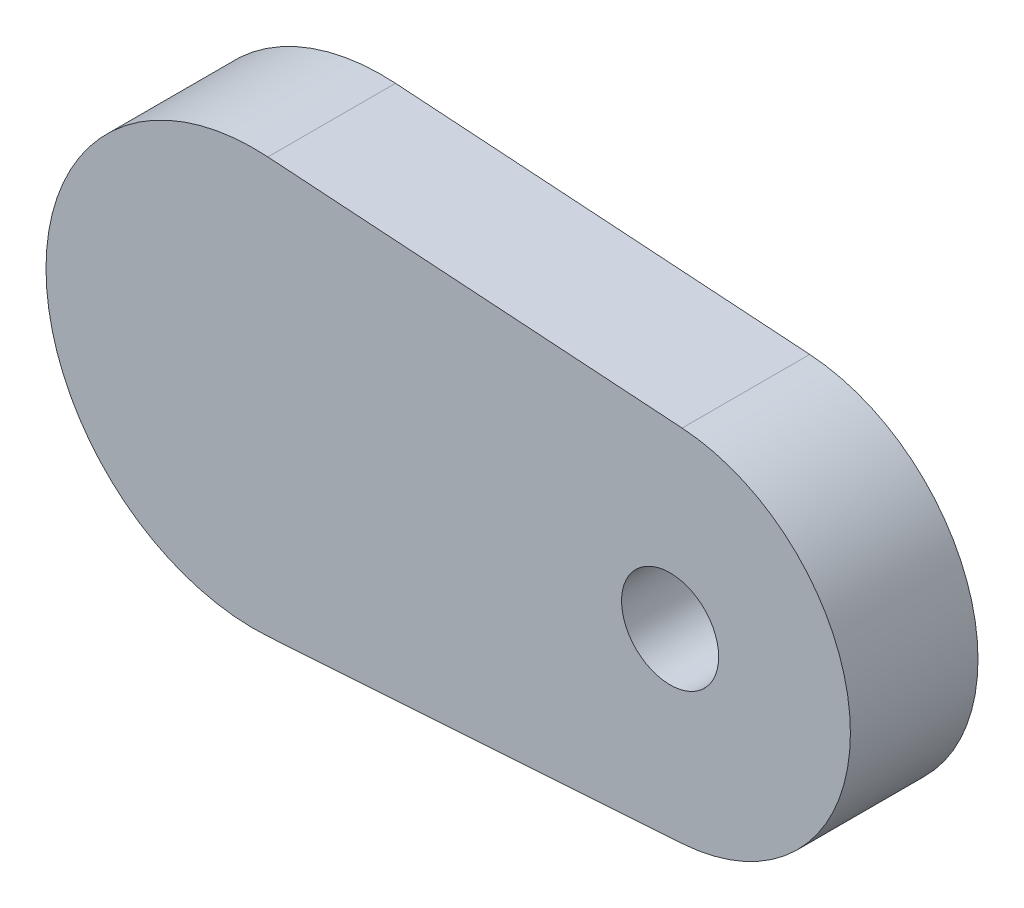
SolidWorks part; units mm, degrees
ref_plane "Front Plane" through (0, 0, 0) normal (0, 0, 1) x (1, 0, 0)
ref_plane "Top Plane" through (0, 0, 0) normal (0, 1, 0) x (1, 0, 0)
ref_plane "Right Plane" through (0, 0, 0) normal (1, 0, 0) x (0, 0, -1)
sketch "Sketch1" plane through (0, 0, 0) normal (0, 0, 1) x (1, 0, 0)
  line L0 (18.0567, 10.0424) -> (32.9901, 11.0401)
  line L1 (32.9901, 24.0112) -> (18.0567, 25.009)
  circle A0 centre (32.5567, 17.5257) radius 1.75
  arc A1 (18.0567, 25.009) -> (18.0567, 10.0424) centre (17.5567, 17.5257) ccw
  arc A2 (32.9901, 11.0401) -> (32.9901, 24.0112) centre (32.5567, 17.5257) ccw
extrude "Extrude1" add sketch "Sketch1" along normal blind 4.6
